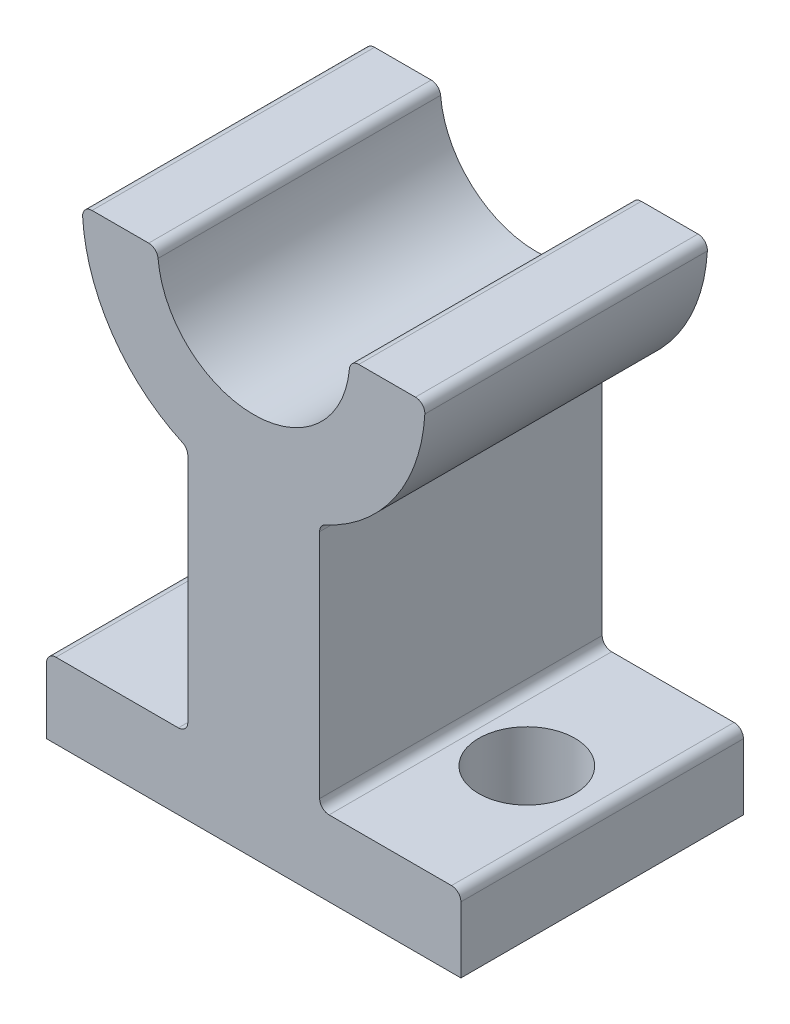
SolidWorks part; units mm, degrees
ref_plane "Alzado" through (0, 0, 0) normal (0, 0, 1) x (1, 0, 0)
ref_plane "Planta" through (0, 0, 0) normal (0, 1, 0) x (1, 0, 0)
ref_plane "Vista lateral" through (0, 0, 0) normal (1, 0, 0) x (0, 0, -1)
sketch "Croquis1" plane through (0, 0, 0) normal (0, 0, 1) x (1, 0, 0)
  line L0 (-3.5, 2) -> (3.5, 15.1) construction
  line L1 (-11, 2) -> (-3.5, 2)
  line L2 (-11, 2) -> (-11, -2)
  line L3 (-11, -2) -> (11, -2)
  line L4 (11, 2) -> (11, -2)
  line L5 (-11, 2) -> (11, -2) construction
  line L6 (-11, -2) -> (11, 2) construction
  line L8 (-3.5, 2) -> (-3.5, 15.1)
  line L10 (3.5, 2) -> (3.5, 15.1)
  line L11 (-3.5, 15.1) -> (3.5, 2) construction
  line L12 (-9.1, 23.5) -> (-5.1, 23.5)
  line L13 (5.1, 23.5) -> (9.1, 23.5)
  line L14 (3.5, 2) -> (11, 2)
  arc A0 (-9.1, 23.5) -> (-3.5, 15.1) centre (0, 23.5) ccw
  arc A1 (-5.1, 23.5) -> (5.1, 23.5) centre (0, 23.5) ccw
  arc A3 (3.5, 15.1) -> (9.1, 23.5) centre (0, 23.5) ccw
  point P0 (0, 0)
  point P12 (0, 0)
  point P13 (0, 8.55)
  dimension "D1" = 10.2
  dimension "D2" = 18.2
  dimension "D5" = 22
  dimension "D3" = 13.1
  dimension "D4" = 7
  dimension "D6" = 4
extrude "Saliente-Extruir1" add sketch "Croquis1" along normal blind 15
fillet "Redondeo1" radius 0.5 4 edges at (3.5, 2, 7.5) (-3.5, 2, 7.5) (-3.5, 15.1, 7.5) (3.5, 15.1, 7.5)
fillet "Redondeo2" radius 0.5 6 edges at (5.1, 23.5, 7.5) (-5.1, 23.5, 7.5) (11, 2, 7.5) (-11, 2, 7.5) (-9.1, 23.5, 7.5) (9.1, 23.5, 7.5)
sketch "Croquis3" plane through (0, -2, 0) normal (0, -1, 0) x (1, 0, 0)
  line L0 (-11, 0) -> (11, 0) construction
  line L1 (-3, 15) -> (3, 15) construction
  line L2 (-3, 15) -> (-3, 0) construction
  line L3 (-3, 0) -> (3, 0) construction
  line L4 (3, 15) -> (3, 0) construction
  line L5 (-3, 15) -> (3, 0) construction
  line L6 (-3, 0) -> (3, 15) construction
  line L7 (-11, 15) -> (11, 15) construction
  line L8 (-11, 15) -> (-11, 0) construction
  line L9 (0, 15) -> (0, 0) construction
  circle A0 centre (-7, 7.5) radius 2.55
  circle A3 centre (7, 7.5) radius 2.55
  point P0 (0, 7.5)
  dimension "D2" = 5.1
  dimension "D1" = 6
  dimension "D3" = 4
  dimension "D5" = 7.5
extrude "Cortar-Extruir1" cut sketch "Croquis3" against normal blind 6
